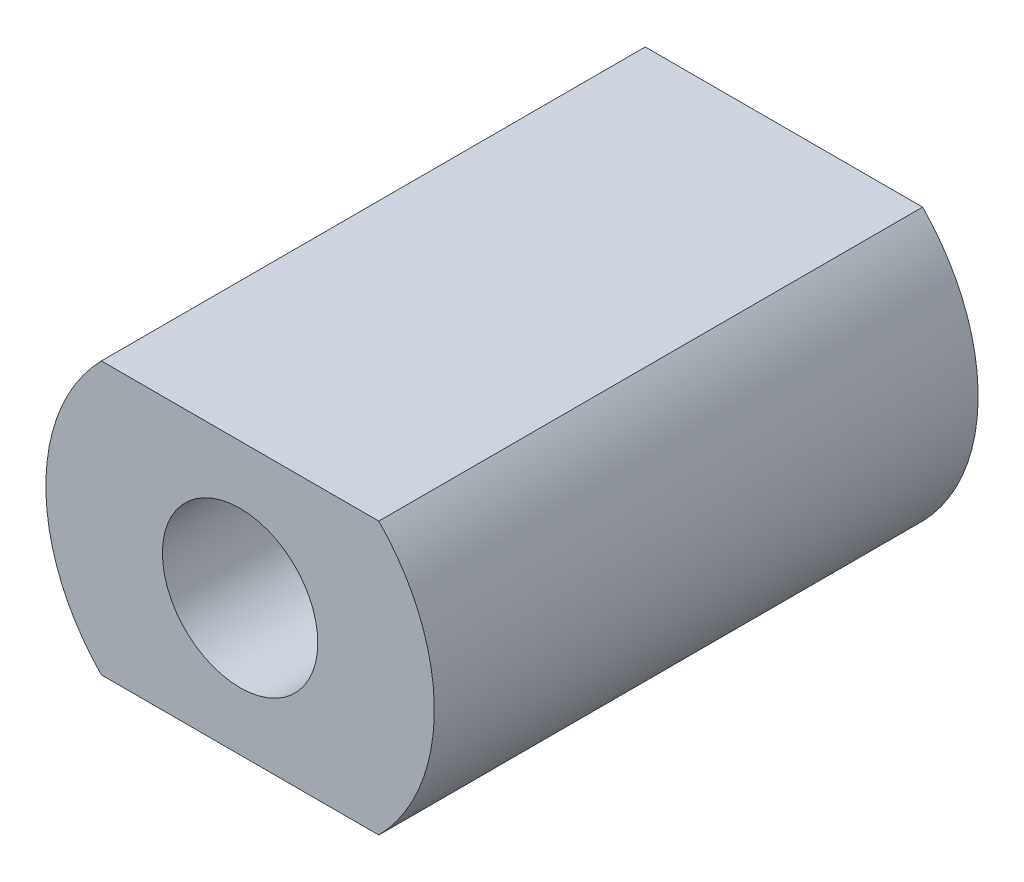
SolidWorks part; units mm, degrees
ref_plane "Front Plane" through (0, 0, 0) normal (0, 0, 1) x (1, 0, 0)
ref_plane "Top Plane" through (0, 0, 0) normal (0, 1, 0) x (1, 0, 0)
ref_plane "Right Plane" through (0, 0, 0) normal (1, 0, 0) x (0, 0, -1)
sketch "Sketch1" plane through (0, 0, 0) normal (0, 0, 1) x (1, 0, 0)
  line L0 (-1.7854, 1.75) -> (1.7854, 1.75)
  line L1 (-1.7854, -1.75) -> (1.7854, -1.75)
  arc A0 (-1.7854, 1.75) -> (-1.7854, -1.75) centre (0, 0) ccw
  arc A1 (1.7854, -1.75) -> (1.7854, 1.75) centre (0, 0) ccw
  circle A2 centre (0, 0) radius 1
  dimension "D1" = 5
  dimension "D2" = 3.5
extrude "Boss-Extrude1" add sketch "Sketch1" along normal blind 7
